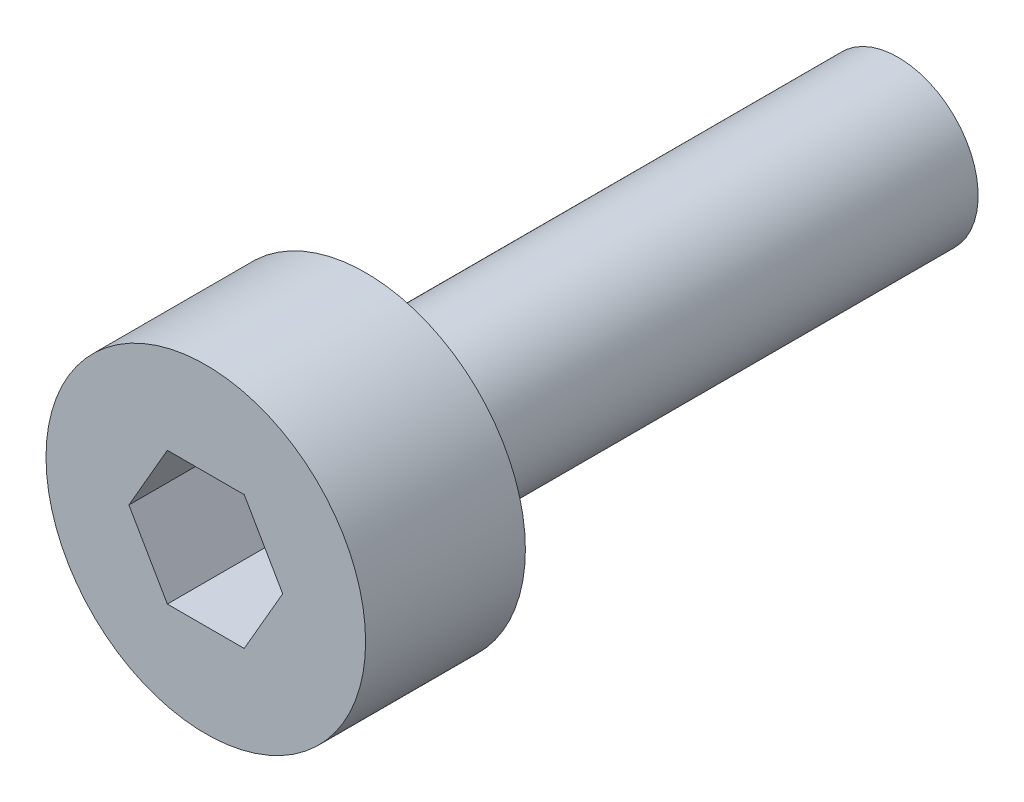
SolidWorks part; units mm, degrees
ref_plane "正面" through (0, 0, 0) normal (0, 0, 1) x (1, 0, 0)
ref_plane "平面" through (0, 0, 0) normal (0, 1, 0) x (1, 0, 0)
ref_plane "右側面" through (0, 0, 0) normal (1, 0, 0) x (0, 0, -1)
sketch "ｽｹｯﾁ5" plane through (0, 0, 0) normal (0, 0, 1) x (1, 0, 0)
  circle A0 centre (0, 0) radius 3
  dimension "D1" = 6
extrude "ﾎﾞｽ - 押し出し1" add sketch "ｽｹｯﾁ5" along normal blind 3
sketch "ｽｹｯﾁ6" plane through (0, 0, 3) normal (0, 0, 1) x (1, 0, 0)
  line L1 (1.4434, 0) -> (0.7217, 1.25)
  line L2 (0.7217, 1.25) -> (-0.7217, 1.25)
  line L3 (-0.7217, 1.25) -> (-1.4434, 0)
  line L4 (-1.4434, 0) -> (-0.7217, -1.25)
  line L5 (-0.7217, -1.25) -> (0.7217, -1.25)
  line L6 (0.7217, -1.25) -> (1.4434, 0)
  circle A0 centre (0, 0) radius 1.25 construction
  dimension "D1" = 2.5
extrude "ｶｯﾄ - 押し出し1" cut sketch "ｽｹｯﾁ6" against normal blind 2
sketch "ｽｹｯﾁ7" plane through (0, 0, 0) normal (0, 0, -1) x (-1, 0, 0)
  circle A0 centre (0, 0) radius 1.5
  dimension "D1" = 3
extrude "ﾎﾞｽ - 押し出し2" add sketch "ｽｹｯﾁ7" along normal blind 10
